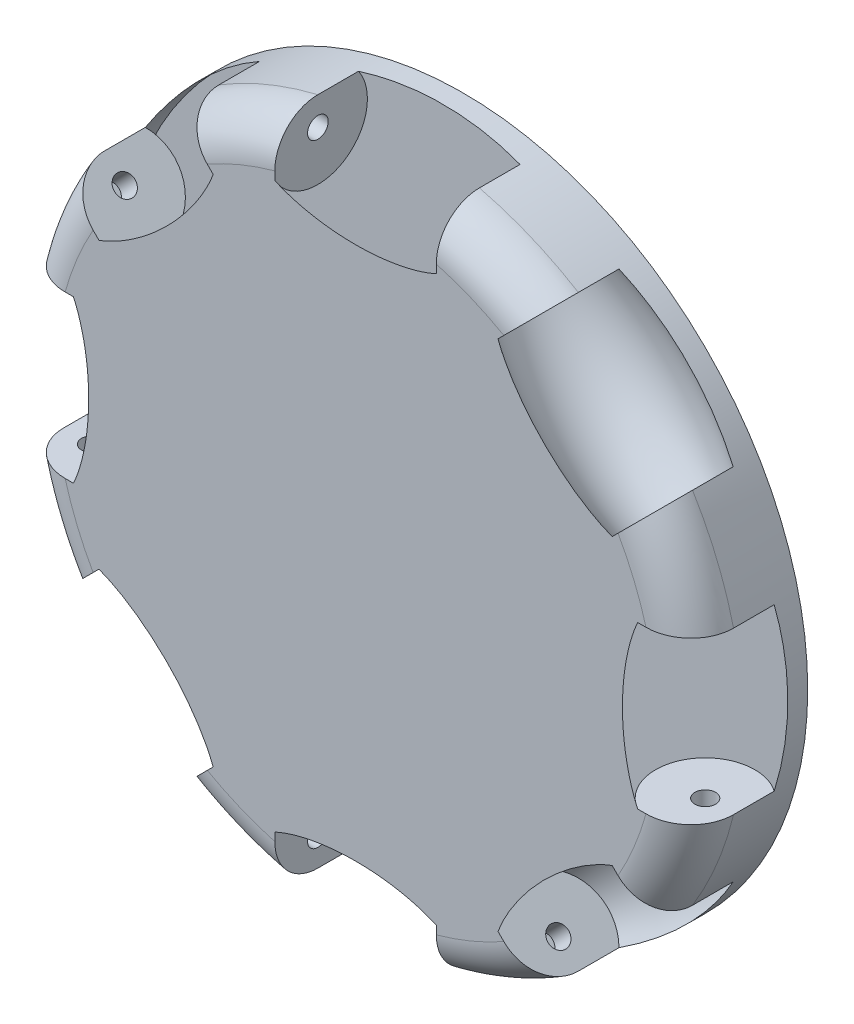
SolidWorks part; units mm, degrees
ref_plane "Front Plane" through (0, 0, 0) normal (0, 0, 1) x (1, 0, 0)
ref_plane "Top Plane" through (0, 0, 0) normal (0, 1, 0) x (1, 0, 0)
ref_plane "Right Plane" through (0, 0, 0) normal (1, 0, 0) x (0, 0, -1)
sketch "Sketch1" plane through (0, 0, 0) normal (0, 0, 1) x (1, 0, 0)
  circle A0 centre (0, 0) radius 25.4
  point P6 (-12.0183, -8.0692)
  point P7 (-18.8859, -8.736)
  point P11 (0, 0)
  point P12 (0, 0)
  dimension "D1" = 50.8
extrude "Boss-Extrude1" add sketch "Sketch1" along normal blind 7.9375
fillet "Fillet1" radius 3.175 1 edges at (25.4, 0, 7.9375)
ref_plane "Plane1" through (0, 0, 4.7625) normal (0, 0, 1) x (1, 0, 0)
sketch "Sketch5" plane through (0, 0, 4.7625) normal (0, 0, 1) x (1, 0, 0)
  line L0 (-5.9531, 26.2576) -> (-5.9531, 22.606)
  line L1 (-5.9531, 22.606) -> (5.9531, 22.606)
  line L2 (5.9531, 22.606) -> (5.9531, 26.2576)
  arc A2 (-5.9531, 26.2576) -> (5.9531, 26.2576) centre (0, 0) cw
  point P2 (0, 26.924)
  point P7 (0, 22.606)
  dimension "D1" = 11.9062
  dimension "D2" = 4.318
  dimension "D3" = 22.606
revolve "Cut-Revolve5" cut sketch "Sketch5" angle 360 about L1
sketch "Sketch6" plane through (0, 0, 0) normal (1, 0, 0) x (0, 0, -1)
  arc A0 (-7.9375, 20.8022) -> (-1.7657, 24.6925) centre (-4.7625, 22.606) ccw construction
  circle A1 centre (-4.7625, 22.606) radius 0.762
  point P4 (-4.7625, 22.606)
  dimension "D1" = 1.524
extrude "Cut-Extrude2" cut sketch "Sketch6" against normal mid plane 15.24
pattern_circular "CirPattern1" count 8 over 360 about axis through (0, 0, 0) along (0, 0, 1) of "Cut-Revolve5", "Cut-Extrude2"
